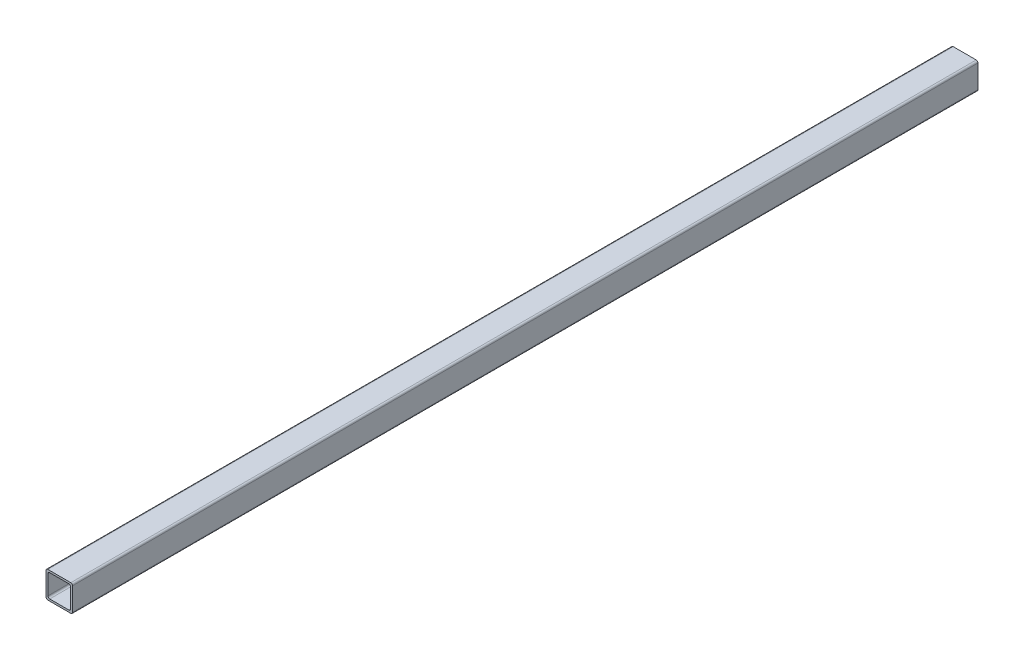
SolidWorks part; units mm, degrees
material "ASTM A500 Grade B"
ref_plane "Front Plane" through (0, 0, 0) normal (0, 0, 1) x (1, 0, 0)
ref_plane "Top Plane" through (0, 0, 0) normal (0, 1, 0) x (1, 0, 0)
ref_plane "Right Plane" through (0, 0, 0) normal (1, 0, 0) x (0, 0, -1)
sketch "Sketch1" plane through (0, 0, 0) normal (0, 0, 1) x (1, 0, 0)
  line L0 (5.3086, -2.7686) -> (32.7914, -2.7686)
  line L1 (2.54, 0) -> (35.56, 0)
  line L2 (0, -2.54) -> (0, -35.56)
  line L3 (2.54, -38.1) -> (35.56, -38.1)
  line L4 (38.1, -2.54) -> (38.1, -35.56)
  line L5 (35.3314, -5.3086) -> (35.3314, -32.7914)
  line L6 (5.3086, -35.3314) -> (32.7914, -35.3314)
  line L7 (2.7686, -5.3086) -> (2.7686, -32.7914)
  line L8 (0, 0) -> (0, -38.1) construction
  line L9 (0, -38.1) -> (38.1, -38.1) construction
  line L10 (38.1, 0) -> (38.1, -38.1) construction
  line L11 (2.7686, -2.7686) -> (2.7686, -35.3314) construction
  line L12 (2.7686, -35.3314) -> (35.3314, -35.3314) construction
  line L13 (35.3314, -2.7686) -> (35.3314, -35.3314) construction
  line L14 (2.7686, -2.7686) -> (35.3314, -2.7686) construction
  line L15 (0, 0) -> (38.1, 0) construction
  arc A0 (0, -35.56) -> (2.54, -38.1) centre (2.54, -35.56) ccw
  arc A1 (38.1, -35.56) -> (35.56, -38.1) centre (35.56, -35.56) cw
  arc A2 (2.7686, -32.7914) -> (5.3086, -35.3314) centre (5.3086, -32.7914) ccw
  arc A3 (32.7914, -35.3314) -> (35.3314, -32.7914) centre (32.7914, -32.7914) ccw
  arc A4 (35.3314, -5.3086) -> (32.7914, -2.7686) centre (32.7914, -5.3086) ccw
  arc A5 (38.1, -2.54) -> (35.56, 0) centre (35.56, -2.54) ccw
  arc A6 (0, -2.54) -> (2.54, 0) centre (2.54, -2.54) cw
  arc A7 (5.3086, -2.7686) -> (2.7686, -5.3086) centre (5.3086, -5.3086) ccw
  point P12 (0, -38.1)
  dimension "D4" = 2.54
  dimension "D3" = 2.7686
extrude "Boss-Extrude1" add sketch "Sketch1" along normal blind 1500
sketch "Sketch2" plane through (0, 0, 0) normal (-1, 0, 0) x (0, 0, 1)
  line L1 (0, -38.1) -> (-432.2243, -38.1)
  line L2 (0, -38.1) -> (0, 1038.8509)
  line L3 (0, 1038.8509) -> (-432.2243, 1038.8509)
  line L4 (-432.2243, -38.1) -> (-432.2243, 1038.8509)
  line L5 (1296.9357, 791.7415) -> (2205.4746, 791.7415)
  line L6 (1296.9357, 791.7415) -> (1296.9357, -925.7285)
  line L7 (1296.9357, -925.7285) -> (2205.4746, -925.7285)
  line L8 (2205.4746, 791.7415) -> (2205.4746, -925.7285)
extrude "Cut-Extrude3" cut sketch "Sketch2" against normal through all both and the other way through all
